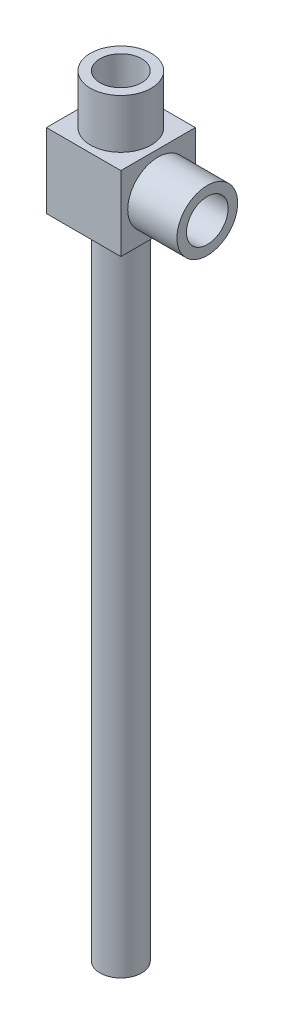
SolidWorks part; units mm, degrees
ref_plane "Alzado" through (0, 0, 0) normal (0, 0, 1) x (1, 0, 0)
ref_plane "Planta" through (0, 0, 0) normal (0, 1, 0) x (1, 0, 0)
ref_plane "Vista lateral" through (0, 0, 0) normal (1, 0, 0) x (0, 0, -1)
ref_plane "Plano1" through (0, -12.7, 0) normal (0, 1, 0) x (1, 0, 0)
sketch "Croquis2" plane through (0, -12.7, 0) normal (0, 1, 0) x (1, 0, 0)
  circle A0 centre (0, -37.25) radius 12.7
extrude "Saliente-Extruir1" add sketch "Croquis2" against normal blind 394.55
sketch "Croquis4" plane through (0, -12.7, 0) normal (0, 1, 0) x (1, 0, 0)
  line L7 (22.7, -14.55) -> (-22.7, -14.55)
  line L8 (22.7, -14.55) -> (22.7, -59.95)
  line L9 (22.7, -59.95) -> (-22.7, -59.95)
  line L10 (-22.7, -14.55) -> (-22.7, -59.95)
  point P0 (0, -37.25)
  point P5 (0, -37.25)
extrude "Saliente-Extruir2" add sketch "Croquis4" along normal blind 45.4
ref_plane "Plano2" through (22.7, 0, 0) normal (1, 0, 0) x (0, 0, -1)
sketch "Croquis5" plane through (22.7, 0, 0) normal (1, 0, 0) x (0, 0, -1)
  circle A0 centre (-37.25, 10) radius 12.7
  circle A1 centre (-37.25, 10) radius 18.5
extrude "Saliente-Extruir3" add sketch "Croquis5" along normal blind 30
sketch "Croquis7" plane through (0, -12.7, 0) normal (0, 1, 0) x (1, 0, 0)
  circle A0 centre (0, -37.25) radius 12.7
  circle A1 centre (0, -37.25) radius 18.5
extrude "Saliente-Extruir4" add sketch "Croquis7" along normal blind 75.4
